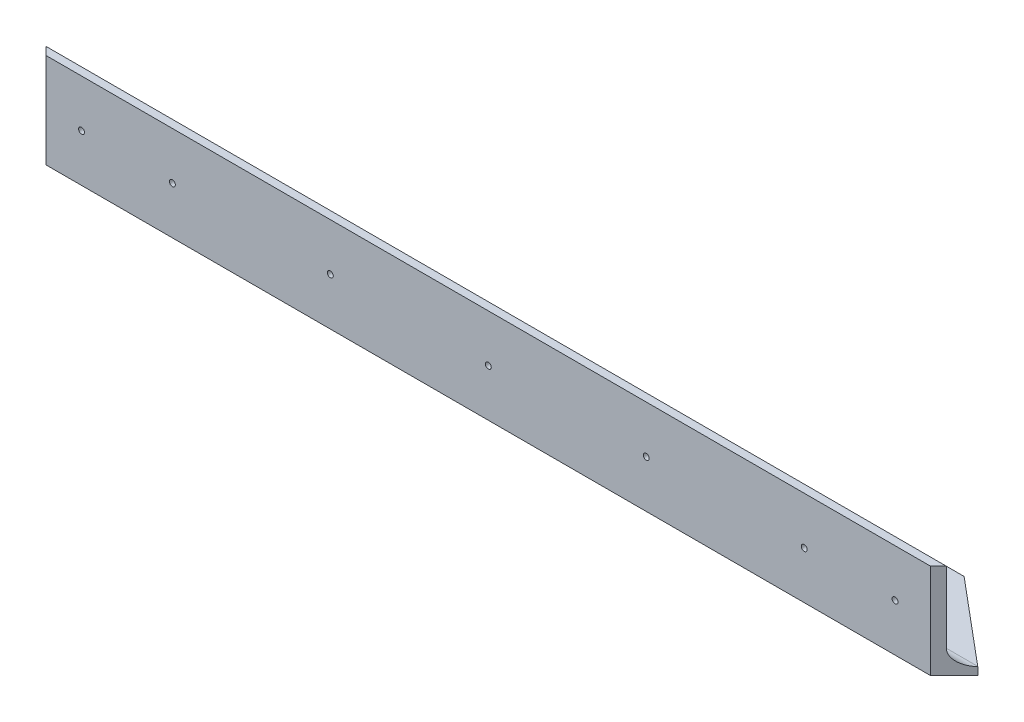
SolidWorks part; units mm, degrees
material "6061-T6 (SS)"
ref_plane "Front" through (0, 0, 0) normal (0, 0, 1) x (1, 0, 0)
ref_plane "Top" through (0, 0, 0) normal (0, 1, 0) x (1, 0, 0)
ref_plane "Right" through (0, 0, 0) normal (1, 0, 0) x (0, 0, -1)
sketch "Sketch1" plane through (0, 0, 0) normal (1, 0, 0) x (0, 0, -1)
  line L0 (0, 0) -> (76.2, 0)
  line L1 (76.2, 0) -> (76.2, 6.35)
  line L2 (76.2, 6.35) -> (6.35, 6.35)
  line L3 (6.35, 6.35) -> (6.35, 76.2)
  line L4 (6.35, 76.2) -> (0, 76.2)
  line L5 (0, 76.2) -> (0, 0)
  dimension "D1" = 76.2
  dimension "D2" = 76.2
  dimension "D3" = 6.35
  dimension "D4" = 6.35
extrude "Boss-Extrude1" add sketch "Sketch1" along normal blind 838.2
fillet "Fillet1" radius 12.7 1 edges at (419.1, 6.35, -6.35)
hole_wizard "17/64 (0.26563) Diameter Hole1" positions "Sketch2" profile "Sketch3" hole size "17/64" standard "ANSI Inch" end condition through all
sketch "Sketch2" plane through (0, 6.35, 0) normal (0, 1, 0) x (1, 0, 0)
  line L0 (838.2, 0) -> (0, 0) construction
  line L1 (838.2, 76.2) -> (0, 76.2) construction
  point P0 (101.6, 44.45)
  point P7 (419.1, 76.2)
  dimension "D1" = 44.45
  dimension "D2" = 317.5
sketch "Sketch3" plane through (101.6, 6.35, -44.45) normal (1, 0, 0) x (0, 0, 1)
  line L0 (0, 0) -> (0, 6.35)
  line L1 (0, 6.35) -> (3.3735, 6.35)
  line L2 (3.3735, 6.35) -> (3.3735, 0)
  line L5 (3.3735, 0) -> (0, 0)
  line L11 (0, -6.35) -> (0, 107.95) construction
  dimension "Thru Hole Dia." = 6.747
  dimension "Thru Hole Depth" = 6.35
pattern_linear "LPattern1" count 6 spacing 127 along (1, 0, 0) of "17/64 (0.26563) Diameter Hole1"
sketch "Sketch7" plane through (0, 0, 0) normal (0, -1, 0) x (1, 0, 0)
  line L0 (63.5, 0) -> (-28.0525, 0)
  line L1 (-28.0525, 0) -> (-28.0525, -91.5525)
  line L2 (-28.0525, -91.5525) -> (63.5, 0)
  line L3 (838.2, 0) -> (0, 0) construction
  point P5 (419.1, 0)
  dimension "D1" = 0
  dimension "D2" = 355.6
  dimension "D3" = 45
extrude "Cut-Extrude3" cut sketch "Sketch7" against normal through all
sketch "Sketch8" plane through (0, 0, 0) normal (0, -1, 0) x (1, 0, 0)
  line L0 (774.7, 0) -> (864.3252, 0)
  line L1 (864.3252, 0) -> (864.3252, -89.6252)
  line L2 (864.3252, -89.6252) -> (774.7, 0)
  line L3 (838.2, 0) -> (63.5, 0) construction
  line L4 (838.2, -76.2) -> (0, -76.2) construction
  point P7 (419.1, -76.2)
  dimension "D1" = 0
  dimension "D2" = 355.6
  dimension "D3" = 45
extrude "Cut-Extrude4" cut sketch "Sketch8" against normal through all
sketch "Sketch9" plane through (0, 0, 0) normal (0, -1, 0) x (-1, 0, 0)
  line L0 (-774.7, 0) -> (-63.5, 0) construction
  circle A0 centre (-419.1, -355.6) radius 571.5
  circle A1 centre (-419.1, -355.6) radius 609.6
  point P4 (-419.1, 0)
  dimension "D1" = 0
  dimension "D3" = 1143
  dimension "D4" = 1219.2
  dimension "D2" = 355.6
sketch "Sketch12" plane through (0, 6.35, 0) normal (0, 1, 0) x (1, 0, 0)
  line L0 (44.5491, 18.9509) -> (112.776, 76.2)
  line L1 (838.2, 76.2) -> (0, 76.2) construction
  line L2 (112.776, 76.2) -> (-12.7, 76.2)
  line L3 (-12.7, 76.2) -> (44.5491, 18.9509)
  line L4 (0, 63.5) -> (44.45, 19.05) construction
  point P7 (15.9246, 47.5754)
  dimension "D1" = 180
  dimension "D2" = 0
  dimension "D3" = 80.9625
  dimension "D4" = 95
extrude "Cut-Extrude5" cut sketch "Sketch12" against normal through all
sketch "Sketch14" plane through (0, 6.35, 0) normal (0, 1, 0) x (1, 0, 0)
  line L0 (793.6509, 18.9509) -> (850.9, 76.2)
  line L1 (793.75, 19.05) -> (838.2, 63.5) construction
  line L2 (850.9, 76.2) -> (725.424, 76.2)
  line L3 (725.424, 76.2) -> (793.6509, 18.9509)
  line L4 (838.2, 76.2) -> (112.776, 76.2) construction
  dimension "D1" = 0
  dimension "D2" = 0
  dimension "D3" = 80.9625
  dimension "D4" = 95
extrude "Cut-Extrude6" cut sketch "Sketch14" against normal through all
hole_wizard "3/16 (0.1875) Diameter Hole1" positions "Sketch17" profile "Sketch18" hole size "3/16" standard "ANSI Inch" end condition through all
sketch "Sketch17" plane through (0, 0, -6.35) normal (0, 0, -1) x (-1, 0, 0)
  line L0 (-781.05, 76.2) -> (-57.15, 76.2) construction
  point P0 (-419.1, 38.1)
  point P5 (-419.1, 76.2)
  dimension "D1" = 38.1
  dimension "D2" = 0
sketch "Sketch18" plane through (419.1, 38.1, -6.35) normal (1, 0, 0) x (0, 1, 0)
  line L0 (0, 0) -> (0, 6.35)
  line L1 (0, 6.35) -> (2.3812, 6.35)
  line L2 (2.3812, 6.35) -> (2.3812, 0)
  line L5 (2.3812, 0) -> (0, 0)
  line L11 (0, -6.35) -> (0, 107.95) construction
  dimension "Thru Hole Dia." = 4.7625
  dimension "Thru Hole Depth" = 6.35
pattern_linear "LPattern2" count 3 spacing 127 along (-1, 0, 0) of "3/16 (0.1875) Diameter Hole1"
pattern_linear "LPattern3" count 3 spacing 127 along (1, 0, 0) of "3/16 (0.1875) Diameter Hole1"
hole_wizard "3/16 (0.1875) Diameter Hole3" positions "Sketch25" profile "Sketch26" hole size "3/16" standard "ANSI Inch" end condition through all
sketch "Sketch25" plane through (0, 0, -6.35) normal (0, 0, -1) x (-1, 0, 0)
  line L0 (-781.05, 76.2) -> (-57.15, 76.2) construction
  circle A0 centre (-419.1, 38.1) radius 2.3813 construction
  point P0 (-746.125, 38.1)
  point P2 (-92.075, 38.1)
  dimension "D1" = 38.1
  dimension "D2" = 38.1
  dimension "D3" = 327.025
  dimension "D4" = 327.025
sketch "Sketch26" plane through (746.125, 38.1, -6.35) normal (1, 0, 0) x (0, 1, 0)
  line L0 (0, 0) -> (0, 6.35)
  line L1 (0, 6.35) -> (2.3812, 6.35)
  line L2 (2.3812, 6.35) -> (2.3812, 0)
  line L5 (2.3812, 0) -> (0, 0)
  line L11 (0, -6.35) -> (0, 107.95) construction
  dimension "Thru Hole Dia." = 4.7625
  dimension "Thru Hole Depth" = 6.35
